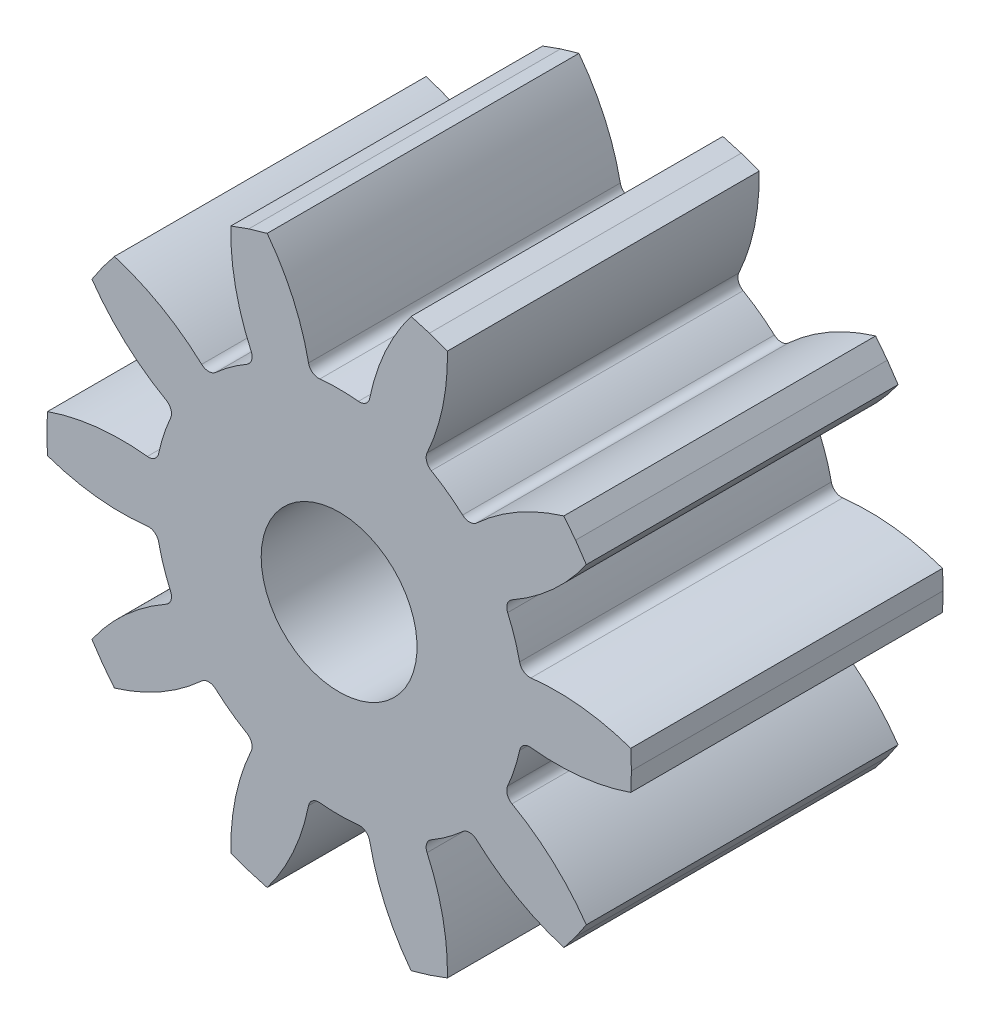
SolidWorks part; units mm, degrees
ref_plane "Front Plane" through (0, 0, 0) normal (0, 0, 1) x (1, 0, 0)
ref_plane "Top Plane" through (0, 0, 0) normal (0, 1, 0) x (1, 0, 0)
ref_plane "Right Plane" through (0, 0, 0) normal (1, 0, 0) x (0, 0, -1)
sketch "Sketch1" plane through (0, 0, 0) normal (0, 0, 1) x (1, 0, 0)
  line L0 (0, 0) -> (74.4139, 0) construction
  line L1 (0, 0) -> (5.6279, 1.8286) construction
  line L2 (0, 0) -> (74.4139, 11.786) construction
  line L3 (0, 0) -> (74.4139, 4.8773) construction
  line L4 (9.3549, 0.6132) -> (9.375, 0)
  line L5 (0, 0) -> (5.6279, -1.8286) construction
  line L6 (0, 0) -> (5.6279, 1.8286)
  line L7 (0, 0) -> (5.6279, -1.8286) construction
  line L8 (0, 0) -> (5.6279, -1.8286)
  line L9 (9.3549, -0.6132) -> (9.375, 0)
  circle A0 centre (0, 0) radius 9.375 construction
  circle A1 centre (0, 0) radius 7.8125 construction
  circle A2 centre (0, 0) radius 5.9175 construction
  arc A3 (5.8446, 0.9257) -> (9.3549, 0.6132) centre (6.9771, -6.2243) cw
  arc A4 (5.8446, 0.9257) -> (5.6279, 1.8286) centre (0, 0) ccw
  arc A5 (5.8446, -0.9257) -> (5.6279, -1.8286) centre (0, 0) cw
  arc A6 (5.8446, -0.9257) -> (9.3549, -0.6132) centre (6.9771, 6.2243) ccw
  dimension "D1" = 18.75
  dimension "D2" = 1.5625
  dimension "D3" = 1.895
  dimension "D4" = 18
  dimension "D5" = 9
  dimension "D6" = 3.75
extrude "Boss-Extrude1" add sketch "Sketch1" along normal blind 10
fillet "Fillet1" radius 0.3325 2 edges at (5.8446, 0.9257, 5) (5.8446, -0.9257, 5)
pattern_circular "CirPattern1" count 10 over 360 about axis through (0, 0, 0) along (0, 0, 1) of "Boss-Extrude1", "Fillet1"
sketch "Sketch2" plane through (0, 0, 0) normal (0, 0, -1) x (-1, 0, 0)
  circle A0 centre (0, 0) radius 2.5
  dimension "D1" = 5
extrude "Cut-Extrude1" cut sketch "Sketch2" against normal up to next
